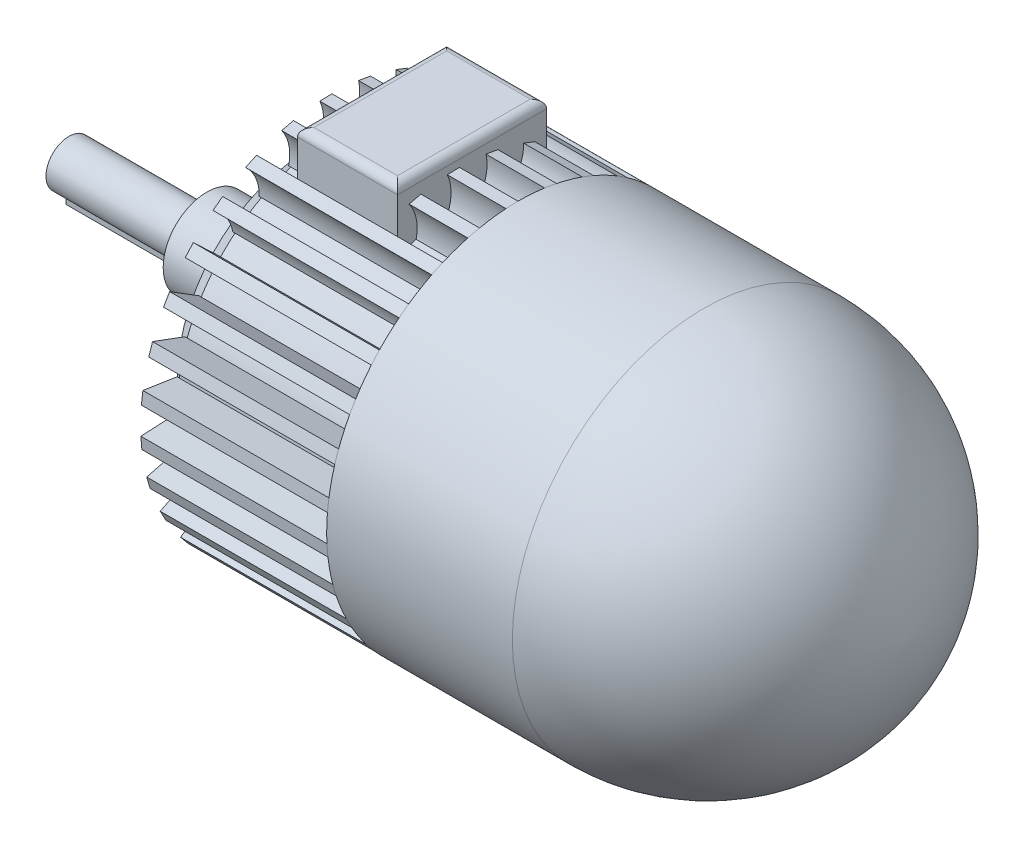
SolidWorks part; units mm, degrees
ref_plane "Front Plane" through (0, 0, 0) normal (0, 0, 1) x (1, 0, 0)
ref_plane "Top Plane" through (0, 0, 0) normal (0, 1, 0) x (1, 0, 0)
ref_plane "Right Plane" through (0, 0, 0) normal (1, 0, 0) x (0, 0, -1)
sketch "Sketch1" plane through (0, 0, 0) normal (0, 0, 1) x (1, 0, 0)
  line L0 (0, 0) -> (129.112, 0) construction
  line L1 (14.8357, 0) -> (14.8357, 6.3271)
  line L2 (14.8357, 6.3271) -> (29.6578, 6.3271)
  line L3 (29.6578, 6.3271) -> (29.6578, 19.0773)
  line L4 (29.6578, 19.0773) -> (33.3235, 22.743)
  line L5 (33.3235, 22.743) -> (60.0026, 22.743)
  line L6 (60.0026, 22.743) -> (60.0026, 27.7634)
  line L7 (60.0026, 27.7634) -> (86.9374, 27.7634)
  line L8 (14.8357, 0) -> (116.0405, 0)
  arc A0 (86.9374, 27.7634) -> (116.0405, 0) centre (86.9374, -1.372) cw
revolve "Revolve1" add sketch "Sketch1" angle 360 about L0
sketch "Sketch2" plane through (60.0026, 0, 0) normal (-1, 0, 0) x (0, 0, 1)
  line L0 (0, 22.743) -> (0, 27.7634)
  line L1 (0, 27.7634) -> (1.7531, 27.708)
  circle A0 centre (0, 0) radius 22.743 construction
  circle A1 centre (0, 0) radius 27.7634 construction
  arc A2 (0, 22.743) -> (1.7531, 22.6753) centre (0, 0) cw
  arc A3 (1.7531, 27.708) -> (1.7531, 22.6753) centre (7.2748, 25.1916) ccw
  circle A4 centre (0, 0) radius 22.743 construction
extrude "Boss-Extrude1" add sketch "Sketch2" along normal blind 27
pattern_circular "CirPattern1" count 31 over 360 about axis through (0, 0, 0) along (1, 0, 0) of "Boss-Extrude1"
ref_plane "Plane1" through (0, 30, 0) normal (0, 1, 0) x (1, 0, 0)
sketch "Sketch3" plane through (0, 30, 0) normal (0, 1, 0) x (1, 0, 0)
  line L0 (33.3235, -8.9688) -> (60.0026, -8.9688) construction
  line L1 (36.9677, 12.6684) -> (51.4952, 12.6684)
  line L2 (36.9677, 12.6684) -> (36.9677, -8.9688)
  line L3 (36.9677, -8.9688) -> (51.4952, -8.9688)
  line L4 (51.4952, 12.6684) -> (51.4952, -8.9688)
extrude "Boss-Extrude2" add sketch "Sketch3" against normal up to next
fillet "Fillet1" radius 1.2 4 edges at (51.4952, 30, -1.8498) (44.2315, 30, -12.6684) (36.9677, 30, -1.8498) (44.2315, 30, 8.9688)
sketch "Sketch4" plane through (14.8357, 0, 0) normal (-1, 0, 0) x (0, 0, 1)
  circle A0 centre (0, 0) radius 3.3302
extrude "Boss-Extrude3" add sketch "Sketch4" along normal blind 20
sketch "Sketch5" plane through (-5.1643, 0, 0) normal (-1, 0, 0) x (0, 0, 1)
  line L1 (-0.6325, -3.2696) -> (0.4051, -3.2696)
  line L2 (-0.6325, -3.2696) -> (-0.6325, -5.0301)
  line L3 (-0.6325, -5.0301) -> (0.4051, -5.0301)
  line L4 (0.4051, -3.2696) -> (0.4051, -5.0301)
  circle A0 centre (0, 0) radius 3.3302 construction
extrude "Boss-Extrude4" add sketch "Sketch5" against normal up to next
